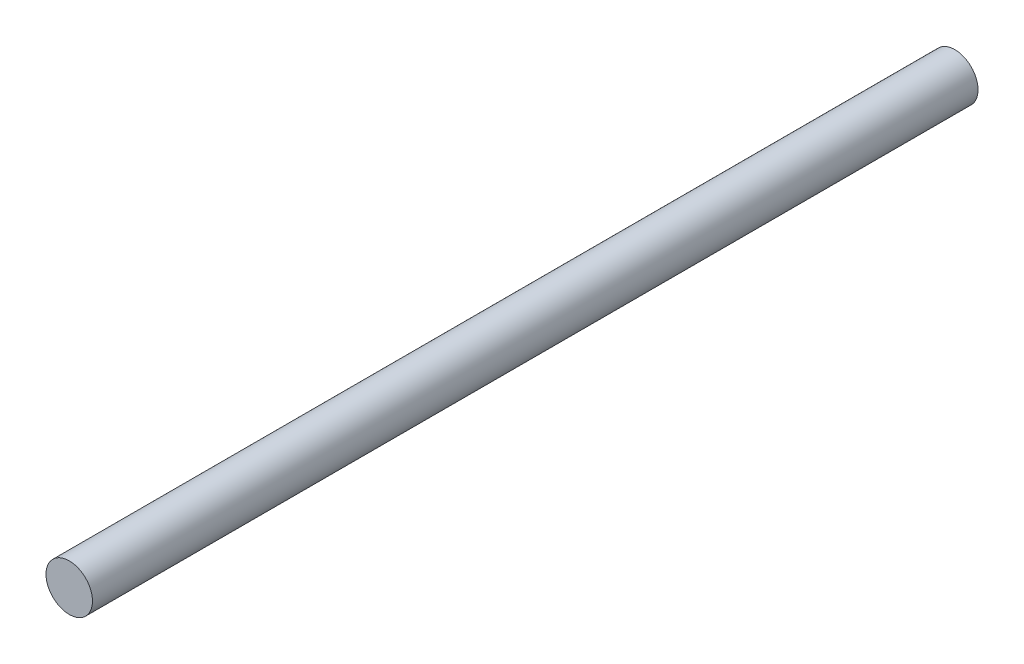
SolidWorks part; units mm, degrees
material "6061-T6 (SS)"
ref_plane "Front Plane" through (0, 0, 0) normal (0, 0, 1) x (1, 0, 0)
ref_plane "Top Plane" through (0, 0, 0) normal (0, 1, 0) x (1, 0, 0)
ref_plane "Right Plane" through (0, 0, 0) normal (1, 0, 0) x (0, 0, -1)
sketch "Sketch1" plane through (0, 0, 0) normal (0, 0, 1) x (1, 0, 0)
  circle A0 centre (0, 0) radius 2
  dimension "D1" = 4
extrude "Boss-Extrude1" add sketch "Sketch1" along normal mid plane 76.2
